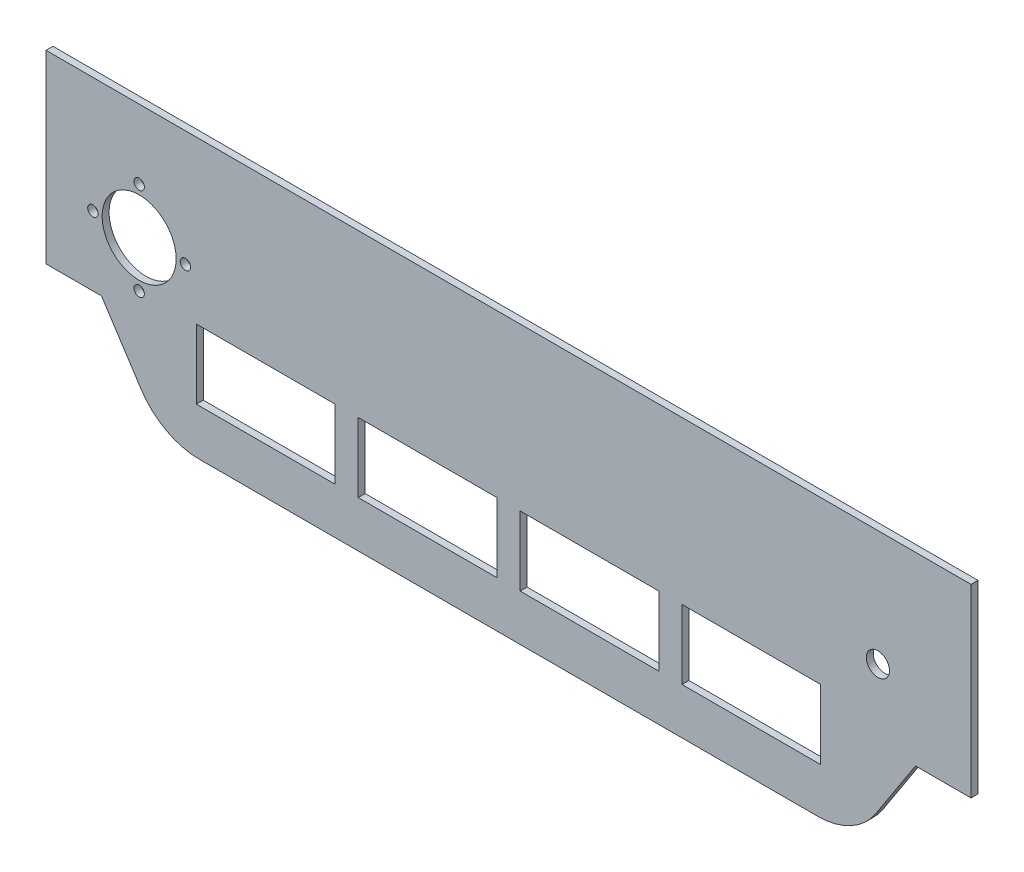
SolidWorks part; units mm, degrees
ref_plane "前基準面" through (0, 0, 0) normal (0, 0, 1) x (1, 0, 0)
ref_plane "上基準面" through (0, 0, 0) normal (0, 1, 0) x (1, 0, 0)
ref_plane "右基準面" through (0, 0, 0) normal (1, 0, 0) x (0, 0, -1)
sketch "草圖1" plane through (0, 0, 0) normal (0, 0, 1) x (1, 0, 0)
  line L0 (55.2806, 100) -> (374.7194, 100)
  line L1 (0, 0) -> (430, 0) construction
  line L2 (0, 0) -> (0, 100) construction
  line L3 (0, 100) -> (430, 100) construction
  line L4 (430, 0) -> (430, 100) construction
  line L5 (399.8727, 53.6503) -> (373.8727, 13.6503)
  line L6 (348.7194, 0) -> (81.2806, 0)
  line L7 (56.1273, 13.6503) -> (30.1273, 53.6503)
  line L8 (215, 0) -> (215, 100) construction
  arc A0 (55.2806, 100) -> (30.1273, 53.6503) centre (55.2806, 70) ccw
  arc A1 (81.2806, 0) -> (56.1273, 13.6503) centre (81.2806, 30) cw
  arc A2 (374.7194, 100) -> (399.8727, 53.6503) centre (374.7194, 70) cw
  arc A3 (373.8727, 13.6503) -> (348.7194, 0) centre (348.7194, 30) cw
  point P14 (65, 0)
  point P20 (365, 0)
  dimension "D4" = 30
  dimension "D1" = 430
  dimension "D2" = 100
  dimension "D3" = 300
extrude "伸長1" add sketch "草圖1" along normal blind 3
sketch "草圖2" plane through (0, 0, 3) normal (0, 0, 1) x (1, 0, 0)
  line L0 (110, 35) -> (210, 35) construction
  line L1 (80, 50) -> (140, 50)
  line L2 (80, 50) -> (80, 20)
  line L3 (80, 20) -> (140, 20)
  line L4 (140, 50) -> (140, 20)
  line L5 (80, 50) -> (140, 20) construction
  line L6 (80, 20) -> (140, 50) construction
  line L7 (150, 50) -> (210, 50)
  line L8 (150, 50) -> (150, 20)
  line L9 (150, 20) -> (210, 20)
  line L10 (210, 50) -> (210, 20)
  line L11 (150, 50) -> (210, 20) construction
  line L12 (150, 20) -> (210, 50) construction
  line L13 (220, 50) -> (280, 50)
  line L14 (220, 50) -> (220, 20)
  line L15 (220, 20) -> (280, 20)
  line L16 (280, 50) -> (280, 20)
  line L17 (220, 50) -> (280, 20) construction
  line L18 (220, 20) -> (280, 50) construction
  line L19 (210, 35) -> (250, 35) construction
  line L20 (140, 50) -> (150, 50) construction
  line L21 (210, 50) -> (220, 50) construction
  line L22 (215, 100) -> (215, 0) construction
  line L23 (250, 35) -> (320, 35) construction
  line L24 (280, 20) -> (290, 20) construction
  line L25 (140, 20) -> (150, 20) construction
  line L26 (210, 20) -> (220, 20) construction
  line L27 (374.7194, 100) -> (55.2806, 100) construction
  line L28 (81.2806, 0) -> (348.7194, 0) construction
  line L29 (280, 50) -> (290, 50) construction
  line L30 (215, 50) -> (215, 80.2047) construction
  line L31 (350, 20) -> (290, 20)
  line L32 (350, 20) -> (350, 50)
  line L33 (350, 50) -> (290, 50)
  line L34 (290, 20) -> (290, 50)
  line L35 (350, 20) -> (290, 50) construction
  line L36 (350, 50) -> (290, 20) construction
  point P0 (110, 35)
  point P10 (250, 35)
  dimension "D1" = 30
  dimension "D2" = 60
  dimension "D3" = 20
  dimension "D4" = 10
extrude "伸長2" cut sketch "草圖2" against normal through all
sketch "草圖3" plane through (0, 0, 3) normal (0, 0, 1) x (1, 0, 0)
  line L0 (55.2806, 70) -> (374.7194, 70) construction
  line L1 (55.2806, 70) -> (35.2806, 70) construction
  line L2 (374.7194, 70) -> (394.7194, 70) construction
  line L4 (374.7194, 90) -> (374.7194, 50) construction
  line L6 (55.2806, 90) -> (55.2806, 50) construction
  circle A0 centre (55.2806, 70) radius 20 construction
  circle A1 centre (374.7194, 70) radius 20 construction
  circle A2 centre (55.2806, 70) radius 16
  circle A3 centre (374.7194, 70) radius 16 construction
  circle A4 centre (55.2806, 90) radius 2.25
  circle A5 centre (75.2806, 70) radius 2.25
  circle A6 centre (55.2806, 50) radius 2.25
  circle A7 centre (35.2806, 70) radius 2.25
  circle A8 centre (374.7194, 50) radius 2.25 construction
  circle A9 centre (394.7194, 70) radius 2.25 construction
  circle A10 centre (374.7194, 90) radius 2.25 construction
  circle A11 centre (354.7194, 70) radius 2.25 construction
  circle A12 centre (374.7194, 70) radius 5
  dimension "D1" = 40
  dimension "D2" = 32
  dimension "D3" = 4.5
  dimension "D4" = 10
extrude "伸長3" cut sketch "草圖3" against normal through all
sketch "草圖4" plane through (0, 0, 3) normal (0, 0, 1) x (1, 0, 0)
  line L0 (373.8727, 13.6503) -> (399.8727, 53.6503) construction
  line L1 (30.1273, 53.6503) -> (56.1273, 13.6503) construction
  line L2 (374.7194, 100) -> (55.2806, 100) construction
  line L3 (391, 40) -> (399.8727, 53.6503)
  line L4 (30.1273, 53.6503) -> (39, 40)
  line L5 (374.7194, 100) -> (55.2806, 100)
  line L6 (15, 40) -> (415, 40) construction
  line L7 (15, 40) -> (15, 120)
  line L8 (15, 120) -> (415, 120)
  line L9 (415, 120) -> (415, 40)
  line L10 (81.2806, 0) -> (348.7194, 0) construction
  line L11 (215, 120) -> (215, 100) construction
  line L12 (15, 40) -> (39, 40)
  line L13 (415, 40) -> (391, 40)
  arc A1 (399.8727, 53.6503) -> (374.7194, 100) centre (374.7194, 70) ccw construction
  arc A2 (55.2806, 100) -> (30.1273, 53.6503) centre (55.2806, 70) ccw construction
  circle A3 centre (55.2806, 70) radius 16 construction
  arc A5 (399.8727, 53.6503) -> (374.7194, 100) centre (374.7194, 70) ccw
  arc A6 (55.2806, 100) -> (30.1273, 53.6503) centre (55.2806, 70) ccw
  circle A7 centre (55.2806, 70) radius 16
  dimension "D1" = 400
  dimension "D2" = 20
  dimension "D3" = 80
extrude "伸長4" add sketch "草圖4" against normal blind 3
